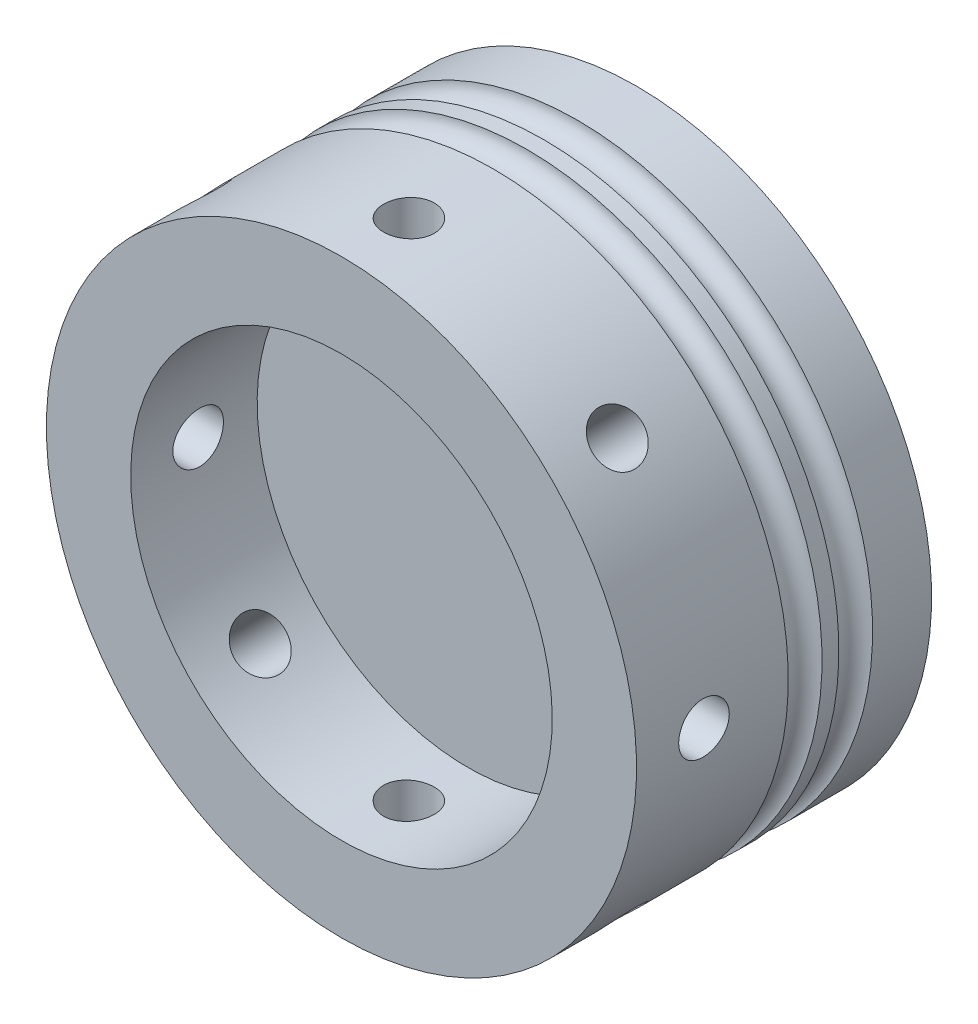
SolidWorks part; units mm, degrees
ref_plane "Front Plane" through (0, 0, 0) normal (0, 0, 1) x (1, 0, 0)
ref_plane "Top Plane" through (0, 0, 0) normal (0, 1, 0) x (1, 0, 0)
ref_plane "Right Plane" through (0, 0, 0) normal (1, 0, 0) x (0, 0, -1)
sketch "Sketch1" plane through (0, 0, 0) normal (1, 0, 0) x (0, 0, -1)
  line L0 (0, 0) -> (0, -10)
  line L1 (0, -10) -> (18, -10)
  line L2 (22, -10) -> (24, -10)
  line L3 (28, -10) -> (35, -10)
  line L4 (35, -10) -> (35, 25)
  line L7 (35, 25) -> (15, 25)
  line L8 (15, 25) -> (15, 0)
  line L9 (15, 0) -> (0, 0)
  arc A0 (18, -10) -> (22, -10) centre (20, -10) cw
  arc A1 (24, -10) -> (28, -10) centre (26, -10) cw
  dimension "D6" = 2
  dimension "D7" = 2
  dimension "D1" = 35
  dimension "D2" = 10
  dimension "D3" = 2
  dimension "D4" = 7
  dimension "D5" = 15
  dimension "D8" = 20
revolve "Revolve1" add sketch "Sketch1" angle 360 about L7
sketch "Sketch2" plane through (0, 0, 0) normal (0, 1, 0) x (1, 0, 0)
  circle A0 centre (0, 8) radius 3
  dimension "D1" = 6
  dimension "D2" = 8
  dimension "D3" = 0
extrude "Cut-Extrude3" cut sketch "Sketch2" against normal mid plane 25
pattern_circular "CirPattern1" count 8 over 360 about axis through (0, 25, -35) along (0, 0, -1) of "Cut-Extrude3"
